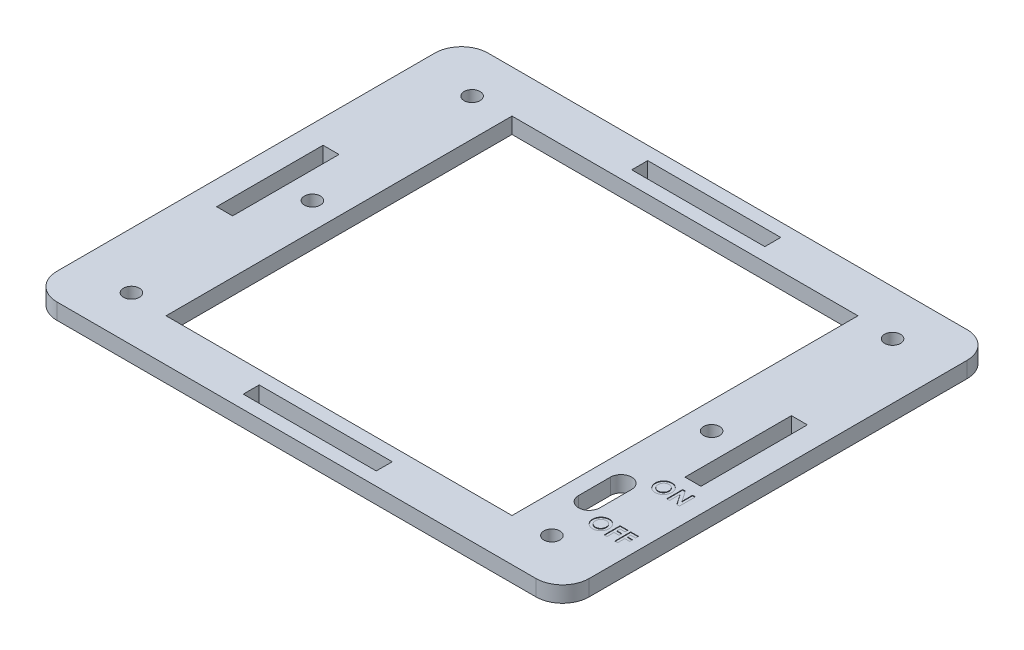
SolidWorks part; units mm, degrees
ref_plane "Front Plane" through (0, 0, 0) normal (0, 0, 1) x (1, 0, 0)
ref_plane "Top Plane" through (0, 0, 0) normal (0, 1, 0) x (1, 0, 0)
ref_plane "Right Plane" through (0, 0, 0) normal (1, 0, 0) x (0, 0, -1)
sketch "Sketch1" plane through (0, 0, 0) normal (0, 1, 0) x (1, 0, 0)
  line L1 (-50, 40.5) -> (50, 40.5)
  line L2 (-50, 40.5) -> (-50, -40.5)
  line L3 (-50, -40.5) -> (50, -40.5)
  line L4 (50, 40.5) -> (50, -40.5)
  line L5 (-50, 40.5) -> (50, -40.5) construction
  line L6 (-50, -40.5) -> (50, 40.5) construction
  point P0 (0, 0)
  dimension "D1" = 100
  dimension "D2" = 81
extrude "Boss-Extrude1" add sketch "Sketch1" along normal blind 3
fillet "Fillet1" radius 5 4 edges at (-50, 1.5, -40.5) (-50, 1.5, 40.5) (50, 1.5, 40.5) (50, 1.5, -40.5)
sketch "Sketch2" plane through (0, 3, 0) normal (0, 1, 0) x (1, 0, 0)
  line L1 (-39.5, 32) -> (39.5, 32) construction
  line L2 (-39.5, 32) -> (-39.5, -32) construction
  line L3 (-39.5, -32) -> (39.5, -32) construction
  line L4 (39.5, 32) -> (39.5, -32) construction
  line L5 (-39.5, 32) -> (39.5, -32) construction
  line L6 (-39.5, -32) -> (39.5, 32) construction
  circle A0 centre (39.5, -32) radius 1.5
  circle A1 centre (39.5, 32) radius 1.5
  circle A2 centre (-39.5, 32) radius 1.5
  circle A3 centre (-39.5, -32) radius 1.5
  point P0 (0, 0)
  dimension "D1" = 3
  dimension "D2" = 64
  dimension "D3" = 79
extrude "Cut-Extrude1" cut sketch "Sketch2" against normal blind 3
sketch "Sketch3" plane through (0, 3, 0) normal (0, 1, 0) x (1, 0, 0)
  line L0 (-44, 0) -> (0, 0) construction
  line L1 (12.5, -35) -> (-12.5, -35)
  line L2 (12.5, -35) -> (12.5, -38)
  line L3 (12.5, -38) -> (-12.5, -38)
  line L4 (-12.5, -35) -> (-12.5, -38)
  line L5 (12.5, -35) -> (-12.5, -38) construction
  line L6 (12.5, -38) -> (-12.5, -35) construction
  line L7 (12.5, 38) -> (-12.5, 38)
  line L8 (12.5, 38) -> (12.5, 35)
  line L9 (12.5, 35) -> (-12.5, 35)
  line L10 (-12.5, 38) -> (-12.5, 35)
  line L11 (12.5, 38) -> (-12.5, 35) construction
  line L12 (12.5, 35) -> (-12.5, 38) construction
  line L13 (45.5, 10) -> (42.5, 10)
  line L14 (45.5, 10) -> (45.5, -10)
  line L15 (45.5, -10) -> (42.5, -10)
  line L16 (42.5, 10) -> (42.5, -10)
  line L17 (45.5, 10) -> (42.5, -10) construction
  line L18 (45.5, -10) -> (42.5, 10) construction
  line L19 (-42.5, 10) -> (-45.5, 10)
  line L20 (-42.5, 10) -> (-42.5, -10)
  line L21 (-42.5, -10) -> (-45.5, -10)
  line L22 (-45.5, 10) -> (-45.5, -10)
  line L23 (-42.5, 10) -> (-45.5, -10) construction
  line L24 (-42.5, -10) -> (-45.5, 10) construction
  line L25 (0, 0) -> (44, 0) construction
  line L26 (0, -36.5) -> (0, 0) construction
  line L27 (0, 0) -> (0, 36.5) construction
  point P0 (0, -36.5)
  point P5 (0, 36.5)
  point P10 (44, 0)
  point P15 (-44, 0)
  dimension "D1" = 3
  dimension "D2" = 25
  dimension "D3" = 20
  dimension "D4" = 70
  dimension "D5" = 85
extrude "Cut-Extrude2" cut sketch "Sketch3" against normal blind 10
sketch "Sketch4" plane through (0, 3, 0) normal (0, 1, 0) x (1, 0, 0)
  line L1 (-32.5, 32.5) -> (32.5, 32.5)
  line L2 (-32.5, 32.5) -> (-32.5, -32.5)
  line L3 (-32.5, -32.5) -> (32.5, -32.5)
  line L4 (32.5, 32.5) -> (32.5, -32.5)
  line L5 (-32.5, 32.5) -> (32.5, -32.5) construction
  line L6 (-32.5, -32.5) -> (32.5, 32.5) construction
  point P0 (0, 0)
  dimension "D1" = 65
  dimension "D2" = 65
extrude "Cut-Extrude3" cut sketch "Sketch4" against normal through all
sketch "Sketch5" plane through (0, 3, 0) normal (0, 1, 0) x (1, 0, 0)
  line L0 (37.5, -17) -> (37.5, -23) construction
  line L1 (39.5, -17) -> (39.5, -23)
  line L2 (35.5, -17) -> (35.5, -23)
  line L4 (37.5, -20) -> (32.5, -20) construction
  line L5 (37.5, -20) -> (42.5, -20) construction
  line L6 (42.5, 10) -> (42.5, -10) construction
  line L7 (32.5, -32.5) -> (32.5, 32.5) construction
  line L9 (12.5, -35) -> (-12.5, -35) construction
  arc A0 (39.5, -17) -> (35.5, -17) centre (37.5, -17) ccw
  arc A1 (35.5, -23) -> (39.5, -23) centre (37.5, -23) ccw
  point P2 (37.5, -20)
  dimension "D1" = 4
  dimension "D2" = 15
  dimension "D3" = 6
extrude "Cut-Extrude4" cut sketch "Sketch5" against normal blind 6
sketch "Sketch6" plane through (0, 3, 0) normal (0, 1, 0) x (1, 0, 0)
  line L0 (-37.5, 0) -> (37.5, 0) construction
  circle A0 centre (-37.5, 0) radius 1.5
  circle A1 centre (37.5, 0) radius 1.5
  dimension "D2" = 3
  dimension "D1" = 75
extrude "Cut-Extrude5" cut sketch "Sketch6" against normal blind 3
sketch "Sketch7" plane through (0, 3, 0) normal (0, 1, 0) x (1, 0, 0)
  text T0 "ON\r\n\r\nOFF" font "Century Gothic" height 3
extrude "Cut-Extrude6" cut sketch "Sketch7" against normal blind 0.1
